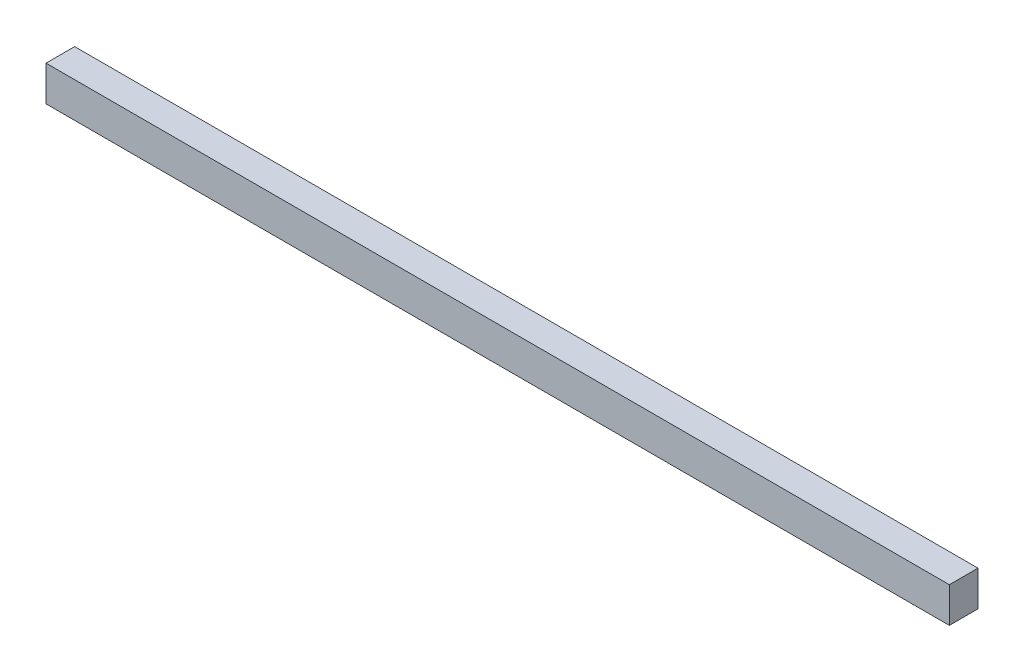
SolidWorks part; units mm, degrees
ref_plane "Front Plane" through (0, 0, 0) normal (0, 0, 1) x (1, 0, 0)
ref_plane "Top Plane" through (0, 0, 0) normal (0, 1, 0) x (1, 0, 0)
ref_plane "Right Plane" through (0, 0, 0) normal (1, 0, 0) x (0, 0, -1)
sketch "Sketch1" plane through (0, 0, 0) normal (0, 0, 1) x (1, 0, 0)
  line L1 (-205, -8) -> (205, -8)
  line L2 (-205, -8) -> (-205, 8)
  line L3 (-205, 8) -> (205, 8)
  line L4 (205, -8) -> (205, 8)
  line L5 (-205, -8) -> (205, 8) construction
  line L6 (-205, 8) -> (205, -8) construction
  point P0 (0, 0)
  dimension "D1" = 16
  dimension "D2" = 410
extrude "Boss-Extrude1" add sketch "Sketch1" against normal blind 13
